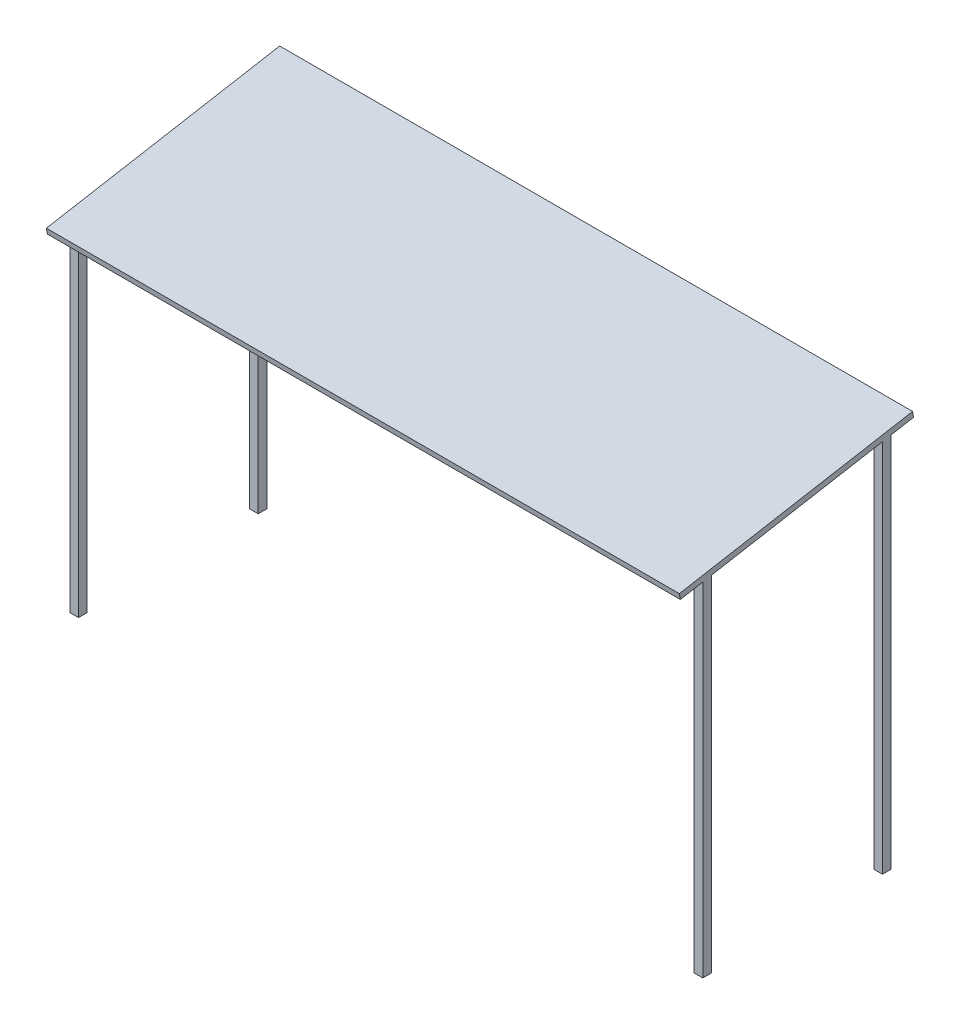
SolidWorks part; units mm, degrees
ref_plane "Alzado" through (0, 0, 0) normal (0, 0, 1) x (1, 0, 0)
ref_plane "Planta" through (0, 0, 0) normal (0, 1, 0) x (1, 0, 0)
ref_plane "Vista lateral" through (0, 0, 0) normal (1, 0, 0) x (0, 0, -1)
sketch "Croquis1" plane through (0, 0, 0) normal (0, 1, 0) x (1, 0, 0)
  line L0 (76.2, 0) -> (2776.2, 0) construction
  line L1 (0, 0) -> (76.2, 0)
  line L2 (0, 0) -> (0, -76.2)
  line L3 (0, -76.2) -> (76.2, -76.2)
  line L4 (76.2, 0) -> (76.2, -76.2)
  line L5 (2776.2, 0) -> (2776.2, -826.2) construction
  line L6 (2776.2, -826.2) -> (0, -826.2) construction
  line L7 (0, -826.2) -> (0, -76.2) construction
  line L8 (5476.2, 0) -> (5476.2, -76.2)
  line L9 (5552.4, -76.2) -> (5476.2, -76.2)
  line L10 (5552.4, 0) -> (5552.4, -76.2)
  line L11 (5552.4, 0) -> (5476.2, 0)
  line L12 (76.2, -1652.4) -> (2776.2, -1652.4) construction
  line L13 (5552.4, -1652.4) -> (5476.2, -1652.4)
  line L14 (5552.4, -1652.4) -> (5552.4, -1576.2)
  line L15 (5552.4, -1576.2) -> (5476.2, -1576.2)
  line L16 (5476.2, -1652.4) -> (5476.2, -1576.2)
  line L17 (76.2, -1652.4) -> (76.2, -1576.2)
  line L18 (0, -1576.2) -> (76.2, -1576.2)
  line L19 (0, -1652.4) -> (0, -1576.2)
  line L20 (0, -1652.4) -> (76.2, -1652.4)
  dimension "D1" = 76.2
  dimension "D2" = 76.2
  dimension "D3" = 2700
  dimension "D4" = 750
extrude "Saliente-Extruir1" add sketch "Croquis1" along normal blind 3300
sketch "Croquis5" plane through (5552.4, 0, 0) normal (1, 0, 0) x (0, 0, -1)
  line L0 (0, 3300) -> (-2183.7175, 2914.9517)
  line L1 (-2183.7175, 2914.9517) -> (-2226.4241, 4680.1948)
  line L2 (-2226.4241, 4680.1948) -> (0, 4614.3785)
  line L3 (0, 4614.3785) -> (0, 3300)
  line L4 (0, 3300) -> (0, 0) construction
  dimension "D1" = 80
extrude "Cortar-Extruir3" cut sketch "Croquis5" against normal up to surface (5552.4 mm away)
sketch "Croquis6" plane through (0, 0, 0) normal (-1, 0, 0) x (0, 0, 1)
  line L0 (0, 3300) -> (1652.4, 3008.6373)
  line L1 (1652.4, 3008.6373) -> (1849.3616, 2973.9077)
  line L2 (0, 3300) -> (-196.9616, 3334.7296)
  line L3 (8.6824, 3349.2404) -> (-188.2791, 3383.97)
  line L4 (8.6824, 3349.2404) -> (1661.0824, 3057.8777)
  line L5 (1661.0824, 3057.8777) -> (1858.044, 3023.148)
  line L6 (1849.3616, 2973.9077) -> (1858.044, 3023.148)
  line L7 (-196.9616, 3334.7296) -> (-188.2791, 3383.97)
  dimension "D1" = 200
  dimension "D2" = 200
  dimension "D3" = 50
extrude "Saliente-Extruir3" add sketch "Croquis6" against normal up to surface (5552.4 mm away) up to face at (5552.4, 1646.641, 38.1)
sketch "Croquis7" plane through (0, 0, 0) normal (0, 0, -1) x (-1, 0, 0)
  line L0 (-76.2, 3300) -> (-76.2, 0) construction
  line L1 (-5476.2, 3300) -> (-76.2, 3300)
  line L2 (-5476.2, 3300) -> (-5476.2, 3223.8)
  line L3 (-5476.2, 3223.8) -> (-76.2, 3223.8)
  line L4 (-76.2, 3300) -> (-76.2, 3223.8)
  dimension "D1" = 76.2
extrude "Saliente-Extruir4" add sketch "Croquis7" against normal up to surface (76.2 mm away) up to face at (5514.3, 1643.2819, 76.2)
sketch "Croquis9" plane through (76.2, 0, 0) normal (1, 0, 0) x (0, 0, -1)
  line L1 (-1652.4, 3008.6373) -> (-1652.4, 0) construction
  line L3 (-1576.2, 3022.0734) -> (-1576.2, 2945.8734)
  line L4 (-1576.2, 2945.8734) -> (-1652.4, 2945.8734)
  line L5 (-1652.4, 3008.6373) -> (-1652.4, 2945.8734)
  line L6 (-1576.2, 3022.0734) -> (-1652.4, 3008.6373)
  dimension "D1" = 76.2
extrude "Saliente-Extruir6" add sketch "Croquis9" along normal up to surface (5400 mm away) up to face at (5476.2, 1507.6777, 1614.3)
